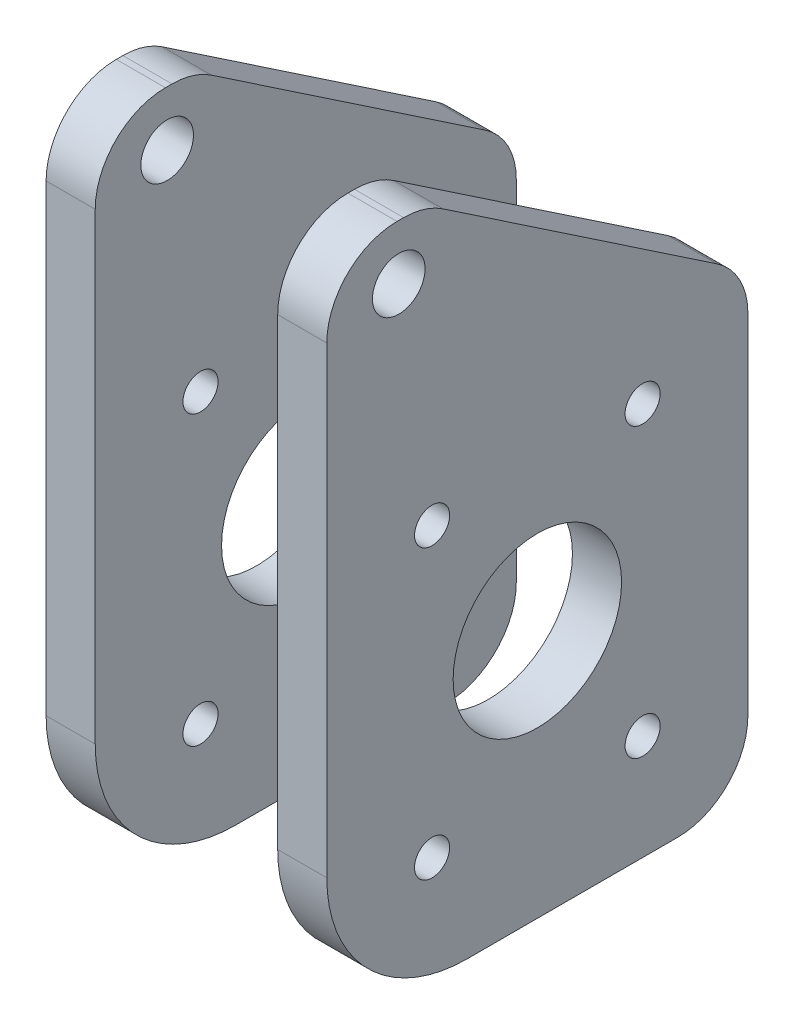
SolidWorks part; units mm, degrees
material "7075-T6, Plate (SS)"
ref_plane "Ground Plane" through (0, 0, 0) normal (0, 0, 1) x (1, 0, 0)
ref_plane "Side Plane" through (0, 0, 0) normal (0, 1, 0) x (1, 0, 0)
ref_plane "Rear Axle Centerline" through (0, 0, 0) normal (1, 0, 0) x (0, 0, -1)
sketch "Chassis Side View" plane through (0, 0, 0) normal (0, 1, 0) x (1, 0, 0)
  line L0 (0, -381) -> (2300, -381) construction
  line L1 (1150, -381) -> (1150, -856.742)
  line L2 (2150, -381) -> (2150, -1062.9307) construction
  line L3 (-753.0356, 0) -> (753.0356, 0) construction
  line L4 (2450, -381) -> (2450, -1062.9307) construction
  dimension "D1" = 2300
  dimension "D2" = 475.742
  dimension "D3" = 1150
  dimension "D4" = 381
  dimension "D5" = 150
  dimension "D6" = 150
ref_plane "Front Axle Centerline" through (2300, 0, 0) normal (1, 0, 0) x (0, 0, -1)
sketch "Front Wheel Assy Constraints" plane through (2300, 0, 0) normal (1, 0, 0) x (0, 0, -1)
  line L0 (0, 727.5) -> (0, 822.5)
  line L1 (0, 822.5) -> (-271.78, 822.5)
  line L2 (-271.78, 822.5) -> (-551.18, 822.5)
  line L3 (-551.18, 822.5) -> (-551.18, 727.5)
  line L4 (-551.18, 775) -> (0, 775) construction
  line L5 (-271.78, 822.5) -> (-271.78, 775) construction
  line L6 (-551.18, 727.5) -> (-445.4516, 727.5)
  line L7 (-445.4516, 727.5) -> (-445.4516, 798.5)
  line L8 (-445.4516, 798.5) -> (-105.7284, 798.5)
  line L9 (-105.7284, 798.5) -> (-105.7284, 727.5)
  line L10 (-105.7284, 727.5) -> (0, 727.5)
  line L11 (0, 0) -> (-673.9047, 0) construction
  line L13 (0, 753.0356) -> (0, -753.0356) construction
  dimension "D1" = 95
  dimension "D2" = 279.4
  dimension "D3" = 271.78
  dimension "D4" = 23.5
  dimension "D5" = 1550
sketch "Front Sus Front View" plane through (2300, 0, 0) normal (1, 0, 0) x (0, 0, -1)
  line L0 (0, 775) -> (0, 768.65) construction
  line L1 (0, 753.0356) -> (0, -753.0356) construction
  line L2 (0, 768.65) -> (-762, 634.2888) construction
  line L3 (0, 768.65) -> (-745.3671, 768.65) construction
  line L4 (-366.7919, -1090.2477) -> (-525.9451, 520.8571) construction
  line L5 (-366.7919, -1090.2477) -> (-379.5678, 520.8571) construction
  line L6 (-366.7919, -1090.2477) -> (0, 775) construction
  line L7 (-525.9451, 520.8571) -> (-541, 673.2571)
  line L8 (-379.5678, 520.8571) -> (-381, 701.4694)
  line L9 (0, 0) -> (-152.4, 0) construction
  line L13 (-525.9451, 520.8571) -> (-379.5678, 520.8571) construction
  dimension "D1" = 6.35
  dimension "D2" = 10
  dimension "D3" = 152.4
  dimension "D4" = 1865.2477
  dimension "D7" = 541
  dimension "D8" = 153.1418
  dimension "D5" = 152.4
ref_plane "Fron Wheel Side View Plane" through (0, 775, 0) normal (0, 1, 0) x (1, 0, 0)
sketch "Front SVSA" plane through (0, 775, 0) normal (0, 1, 0) x (1, 0, 0)
  line L0 (2271.684, -676.7175) -> (2328.316, 133.1575)
  line L1 (2300, 0) -> (2300, -771.0839) construction
  line L2 (2300, 0) -> (-2450.054, -116.0888) construction
  line L3 (-2450.054, -116.0888) -> (2298.2335, -297.0415) construction
  line L4 (-753.0356, 0) -> (753.0356, 0) construction
  point P5 (2300, -271.78)
  dimension "D1" = 4
  dimension "D2" = 1.4
  dimension "D3" = 4750.054
sketch3d "Front Chassis Side Axes"
  line L0 (2300, 520.8571, 379.5678) -> (2300, 701.4694, 381) construction
  line L1 (2300, 520.8571, 525.9451) -> (2300, 673.2571, 541) construction
  line L2 (2300, 520.8571, 379.5678) -> (2300, 701.4694, 381) construction
  line L3 (2300, 520.8571, 525.9451) -> (2300, 673.2571, 541) construction
  line L4 (2300, 673.2571, 541) -> (2300, 775, 551.0507) construction
  line L5 (2300, 701.4694, 381) -> (2300, 775, 381.5831) construction
  line L6 (2300, 775, 0) -> (2300, 775, 771.0839) construction
  line L7 (-2450.054, 775, 116.0888) -> (2349.7917, 775, 555.6101) construction
  line L8 (-2450.054, 775, 116.0888) -> (2349.9221, 775, 384.3734) construction
  line L9 (2349.9221, 775, 384.3734) -> (2177.377, 520.8571, 372.714) construction
  line L10 (2349.7917, 775, 555.6101) -> (2225.4174, 520.8571, 519.1156) construction
  line L11 (2300, 520.8571, 525.9451) -> (2300, 520.8571, 519.1156) construction
  line L12 (2300, 520.8571, 519.1156) -> (2225.4174, 520.8571, 519.1156) construction
  line L13 (2598.7501, 520.8571, 553.3017) -> (1702.4998, 520.8571, 471.2321)
  line L14 (2300, 520.8571, 379.5678) -> (2300, 520.8571, 372.714) construction
  line L15 (2300, 520.8571, 372.714) -> (2177.377, 520.8571, 372.714) construction
  line L16 (2599.5325, 520.8571, 396.3095) -> (1700.935, 520.8571, 346.0843)
  dimension "D1" = 50
  dimension "D2" = 50
  dimension "D3" = 600
  dimension "D4" = 300
  dimension "D5" = 600
  dimension "D6" = 300
sketch3d "Front Left Control Arm"
  line L0 (2300, 520.8571, 379.5678) -> (2300, 701.4694, 381) construction
  line L2 (2300, 520.8571, 379.5678) -> (2300, 701.4694, 381) construction
  line L3 (2300, 520.8571, 525.9451) -> (2300, 673.2571, 541) construction
  line L4 (2598.7501, 520.8571, 553.3017) -> (1702.4998, 520.8571, 471.2321) construction
  line L5 (2599.5325, 520.8571, 396.3095) -> (1700.935, 520.8571, 346.0843) construction
  line L6 (2598.7501, 520.8571, 553.3017) -> (1702.4998, 520.8571, 471.2321) construction
  line L7 (2599.5325, 520.8571, 396.3095) -> (1700.935, 520.8571, 346.0843) construction
  line L8 (2450, 520.8571, 539.6806) -> (2280.5957, 673.2571, 539.2232)
  line L9 (2280.5957, 673.2571, 539.2232) -> (2150, 520.8571, 512.2097)
  line L10 (2300, 520.8571, 525.9451) -> (2300, 673.2571, 541) construction
  line L11 (2300, 673.2571, 541) -> (2280.5957, 673.2571, 539.2232) construction
  line L12 (2271.684, 775, 676.7175) -> (2328.316, 775, -133.1575) construction
  line L13 (2150, 0, 512.2097) -> (2150, 520.8571, 512.2097) construction
  line L14 (2292.3517, 701.4694, 380.5725) -> (2292.3517, 775, 381.1556) construction
  line L15 (2150, 0, 381) -> (2150, 0, 1062.9307) construction
  line L16 (2450, 0, 539.6806) -> (2450, 520.8571, 539.6806) construction
  line L17 (2450, 0, 381) -> (2450, 0, 1062.9307) construction
  line L18 (2450, 520.8571, 387.9517) -> (2292.3517, 701.4694, 380.5725)
  line L19 (2292.3517, 701.4694, 380.5725) -> (2150, 520.8571, 371.1838)
  line L20 (2300, 701.4694, 381) -> (2292.3517, 701.4694, 380.5725) construction
  line L21 (2450, 0, 387.9517) -> (2450, 520.8571, 387.9517) construction
  line L22 (2150, 0, 371.1838) -> (2150, 520.8571, 371.1838) construction
  line L23 (2280.5957, 673.2571, 539.2232) -> (2280.5957, 775, 549.2738) construction
sketch3d "Front Control Arm"
  line L0 (2450, 520.8571, 387.9517) -> (2292.3517, 701.4694, 380.5725) construction
  line L1 (2292.3517, 701.4694, 380.5725) -> (2150, 520.8571, 371.1838) construction
  line L2 (2280.5957, 673.2571, 539.2232) -> (2150, 520.8571, 512.2097) construction
  line L3 (2450, 520.8571, 539.6806) -> (2280.5957, 673.2571, 539.2232) construction
  line L4 (2450, 520.8571, 387.9517) -> (2292.3517, 701.4694, 380.5725)
  line L5 (2292.3517, 701.4694, 380.5725) -> (2150, 520.8571, 371.1838)
  line L6 (2280.5957, 673.2571, 539.2232) -> (2150, 520.8571, 512.2097)
  line L7 (2450, 520.8571, 539.6806) -> (2280.5957, 673.2571, 539.2232)
  line L8 (2450, -520.8571, 539.6806) -> (2280.5957, -673.2571, 539.2232)
  line L9 (2280.5957, -673.2571, 539.2232) -> (2150, -520.8571, 512.2097)
  line L10 (2292.3517, -701.4694, 380.5725) -> (2150, -520.8571, 371.1838)
  line L11 (2450, -520.8571, 387.9517) -> (2292.3517, -701.4694, 380.5725)
ref_plane "Max Droop Plane" through (0, 0, -25.4) normal (0, 0, 1) x (1, 0, 0)
ref_plane "Plane3" through (2292.3517, 0, 0) normal (1, 0, 0) x (0, 0, -1)
sketch "Shock" plane through (2292.3517, 0, 0) normal (1, 0, 0) x (0, 0, -1)
  line L0 (-377.1418, 701.4343) -> (-411.0525, 664.6394) construction
  line L1 (-411.0525, 664.6394) -> (-543.5971, 520.822)
  line L3 (94.8273, 0) -> (-94.8273, 0) construction
  line L4 (-411.0525, -664.6394) -> (-543.5971, -520.822)
  dimension "D1" = 50.038
  dimension "D2" = 195.58
  dimension "D3" = 30.48
  dimension "D4" = 36.83
sketch3d "3DSketch1"
  line L0 (2292.3517, 701.4694, 380.5725) -> (2318.5484, 671.4568, 381.7987) construction
  line L1 (2450, 520.8571, 387.9517) -> (2292.3517, 701.4694, 380.5725) construction
  line L2 (2318.5484, 671.4568, 381.7987) -> (2292.3517, 664.6394, 411.0525) construction
  line L3 (2292.3517, 664.6394, 411.0525) -> (2267.7008, 670.193, 378.9467) construction
  line L4 (2292.3517, 701.4694, 380.5725) -> (2150, 520.8571, 371.1838) construction
  line L5 (2267.7008, 670.193, 378.9467) -> (2292.3517, 701.4694, 380.5725) construction
  line L6 (2318.5484, 671.4568, 381.7987) -> (2267.7008, 670.193, 378.9467) construction
  dimension "D1" = 40.857
  dimension "D2" = 39.8563
sketch3d "Parametric Analysis"
  line L2 (2300, 822.5, 0) -> (2300, 822.5, 271.78) construction
  line L3 (2300.4137, 822.5, 271.7939) -> (2300.4137, 822.5, -88.8537) construction
  line L4 (2450, 520.8571, 387.9517) -> (2292.3526, 701.4695, 380.5568)
  line L5 (2292.3526, 701.4695, 380.5568) -> (2150, 520.8571, 371.1838)
  line L6 (2450, 520.8571, 539.6806) -> (2280.5972, 673.2586, 539.2077)
  line L7 (2280.5972, 673.2586, 539.2077) -> (2150, 520.8571, 512.2097)
  line L8 (2292.3517, 701.4694, 380.5725) -> (2300, 822.5, 271.78) construction
  line L9 (2450, 520.8571, 387.9517) -> (2292.3517, 701.4694, 380.5725) construction
  line L10 (2292.3517, 701.4694, 380.5725) -> (2150, 520.8571, 371.1838) construction
  line L11 (2450, 520.8571, 539.6806) -> (2280.5957, 673.2571, 539.2232) construction
  line L12 (2280.5957, 673.2571, 539.2232) -> (2150, 520.8571, 512.2097) construction
  line L13 (2280.5957, 673.2571, 539.2232) -> (2292.3517, 701.4694, 380.5725) construction
  line L14 (2300, 822.5, 271.78) -> (2280.5957, 673.2571, 539.2232) construction
  line L15 (2300, 822.5, 271.78) -> (2300.4132, 720.8156, 271.78) construction
  line L16 (2280.5972, 673.2586, 539.2077) -> (2300.4137, 822.5, 271.7939) construction
  line L17 (2300.4137, 822.5, 271.7939) -> (2292.3526, 701.4695, 380.5568) construction
  line L18 (2280.5972, 673.2586, 539.2077) -> (2292.3526, 701.4695, 380.5568) construction
  line L19 (2300.4137, 822.5, 271.7939) -> (2300.4137, 720.8148, 271.7641) construction
  line L22 (2292.3517, 520.822, 543.5971) -> (2292.3524, 670.3521, 408.6413)
  line L23 (2292.3524, 670.3521, 408.6413) -> (2292.3526, 701.4695, 380.5568) construction
  line L29 (2292.3524, 670.3521, 408.6413) -> (2321.8231, 667.7059, 381.9392) construction
  line L30 (2321.8231, 667.7059, 381.9392) -> (2292.3526, 701.4695, 380.5568) construction
  line L31 (2271.4781, 674.9846, 379.1823) -> (2292.3526, 701.4695, 380.5568) construction
  line L32 (2271.4781, 674.9846, 379.1823) -> (2321.8231, 667.7059, 381.9392) construction
  line L33 (2292.3524, 670.3521, 408.6413) -> (2271.4781, 674.9846, 379.1823) construction
  line L37 (2318.5484, 671.4568, 381.7987) -> (2267.7008, 670.193, 378.9467) construction
  line L39 (2300.4137, 822.5, 271.7939) -> (2300.4137, 822.5798, 0.014)
  line L40 (2300.4137, 822.5798, 0.014) -> (2300.4137, 727.5798, -0.014)
  line L41 (2300, 727.5, 0) -> (2300, 822.5, 0) construction
  line L46 (2318.5484, 671.4568, 381.7987) -> (2292.3517, 664.6394, 411.0525) construction
  point P5 (2300.4137, 775.0798, 0)
  dimension "D1" = 25.4
  dimension "D3" = 201.4258
  dimension "D4" = 0.017
ref_plane "Plane1" through (0, 724.454, 0) normal (0, 1, 0) x (1, 0, 0)
sketch "Sketch1" plane through (0, 724.454, 0) normal (0, 1, 0) x (1, 0, 0)
  line L0 (2300, 0) -> (2300, -551.18) construction
  line L1 (2300, 0) -> (2300, -673.9047) construction
  line L2 (-753.0356, 0) -> (753.0356, 0) construction
  line L3 (2300, -275.59) -> (2280.5957, -539.2232) construction
  line L4 (2295.0737, -527.2852) -> (2266.1177, -527.2852)
  line L5 (2295.0737, -527.2852) -> (2319.6398, -484.4331)
  line L6 (2319.6398, -484.4331) -> (2343.1517, -404.3723)
  line L7 (2343.1517, -404.3723) -> (2343.1517, -356.7727)
  line L8 (2343.1517, -356.7727) -> (2320.6639, -270.2211)
  line L9 (2266.1177, -527.2852) -> (2241.5517, -484.4331)
  line L10 (2241.5517, -484.4331) -> (2241.5517, -356.7727)
  line L11 (2280.4102, -267.1009) -> (2241.5517, -356.7727)
  line L12 (2332.9917, -380.5725) -> (2251.7117, -380.5725) construction
  line L13 (2343.1517, -356.7727) -> (2241.5517, -356.7727) construction
  line L14 (2332.9917, -365.6119) -> (2251.7117, -365.6119)
  line L15 (2332.9917, -365.6119) -> (2332.9917, -395.5331)
  line L16 (2332.9917, -395.5331) -> (2251.7117, -395.5331)
  line L17 (2251.7117, -365.6119) -> (2251.7117, -395.5331)
  line L18 (2332.9917, -365.6119) -> (2251.7117, -395.5331) construction
  line L19 (2332.9917, -395.5331) -> (2251.7117, -365.6119) construction
  line L20 (2343.1517, -404.3723) -> (2241.5517, -404.3723) construction
  line L21 (2319.6398, -484.4331) -> (2241.5517, -484.4331) construction
  line L22 (2280.5957, -539.2232) -> (2280.5957, -527.2852) construction
  circle A0 centre (2300, -275.59) radius 15
  arc A1 (2320.6639, -270.2211) -> (2280.4102, -267.1009) centre (2300, -275.59) ccw
  arc A2 (2280.4102, -267.1009) -> (2320.6639, -270.2211) centre (2300, -275.59) ccw construction
  point P21 (2292.3517, -380.5725)
  point P30 (2292.3517, -380.5725)
  dimension "D1" = 30
  dimension "D2" = 42.7
  dimension "D3" = 81.28
  dimension "D4" = 29.9212
  dimension "D5" = 10.16
  dimension "D6" = 10.16
  dimension "D7" = 8.8392
  dimension "D8" = 8.8392
  dimension "D9" = 11.938
  dimension "D10" = 28.956
  dimension "D11" = 88.9
ref_plane "Plane4" through (2292.3517, 0, 0) normal (-1, 0, 0) x (0, 0, 1)
sketch "Sketch3" plane through (2292.3517, 0, 0) normal (-1, 0, 0) x (0, 0, 1)
  line L0 (556.6129, 408.838) -> (556.6129, 530.758)
  line L3 (480.4129, 491.388) -> (480.4129, 408.838)
  line L4 (480.4129, 408.838) -> (556.6129, 408.838)
  line L6 (537.5629, 479.958) -> (499.4629, 479.958) construction
  line L13 (556.6129, 530.758) -> (538.8329, 530.758)
  line L14 (538.8329, 530.758) -> (480.4129, 491.388)
  line L16 (537.5629, 479.958) -> (499.4629, 427.888) construction
  line L17 (499.4629, 479.958) -> (537.5629, 427.888) construction
  circle A0 centre (543.5971, 520.822) radius 4.7625
  circle A1 centre (537.5629, 479.958) radius 3.175
  circle A2 centre (537.5629, 427.888) radius 3.175
  circle A3 centre (499.4629, 427.888) radius 3.175
  circle A4 centre (499.4629, 479.958) radius 3.175
  circle A12 centre (518.5129, 453.923) radius 15.24
  point P28 (75.0078, 775.7838)
  dimension "D5" = 9.525
  dimension "D6" = 6.35
  dimension "D7" = 6.35
  dimension "D8" = 6.35
  dimension "D9" = 6.35
  dimension "D18" = 30.48
  dimension "D2" = 82.55
  dimension "D3" = 76.2
  dimension "D4" = 121.92
  dimension "D10" = 17.78
  dimension "D11" = 50.8
  dimension "D12" = 19.05
  dimension "D13" = 19.05
  dimension "D14" = 19.05
  dimension "D15" = 19.05
  dimension "D16" = 19.05
  dimension "D17" = 19.05
extrude "Boss-Extrude1" add sketch "Sketch3" along normal mid plane 50.8
fillet "Fillet1" radius 12.7 4 edges at (2292.3517, 408.838, 480.4129) (2292.3517, 491.388, 480.4129) (2292.3517, 530.758, 538.8329) (2292.3517, 530.758, 556.6129)
fillet "Fillet2" radius 25.4 1 edges at (2292.3517, 408.838, 556.6129)
sketch "Sketch4" plane through (0, 408.838, 0) normal (0, -1, 0) x (1, 0, 0)
  line L0 (2308.8617, 478.8299) -> (2308.8617, 576.5141)
  line L1 (2308.8617, 576.5141) -> (2275.8417, 576.5141)
  line L2 (2275.8417, 576.5141) -> (2275.8417, 478.8299)
  line L3 (2275.8417, 478.8299) -> (2308.8617, 478.8299)
  line L4 (2266.9517, 493.1129) -> (2266.9517, 531.2129) construction
  line L5 (2317.7517, 493.1129) -> (2317.7517, 531.2129) construction
  dimension "D1" = 8.89
  dimension "D2" = 8.89
extrude "Cut-Extrude1" cut sketch "Sketch4" against normal through all
equation "\"wheelbase\"= 2.3m"
equation "\"track_front_outer\"= 1.55m"
equation "\"cg_h\"= 18.73in"
equation "\"cg_b\"= \"wheelbase\" / 2"
equation "\"chassis_ride_height\"= 15in"
equation "\"hub_offset\"= 23.5mm"
equation "\"tire_radius\"= 11in"
equation "\"tire_radius_loaded\"= 10.7in"
equation "\"tire_width\"= 95mm"
equation "\"static_camber\"= 0deg"
equation "\"caster_static\"= 4deg"
equation "\"control_arm_ratio\"= 0.95"
equation "\"roll_center_height\"= 6in"
equation "\"scrub_radius\"= 0.25in"
equation "\"camber_change_rate\"= 0.5deg'per inch of travel"
equation "\"fvsa_length\"= atn ( 1 / \"camber_change_rate\" )"
equation "\"svsa_length\"= 2.5 * \"wheelbase\""
equation "\"svsa_height\"= 1"
equation "\"anti_squat_rear\"= 0.15"
equation "\"front_brakes\"= .75"
equation "\"anti_dive_front\"= 0.1"
equation "\"D1@Chassis Side View\" = \"wheelbase\""
equation "\"D2@Chassis Side View\" = \"cg_h\""
equation "\"D3@Chassis Side View\" = \"cg_b\""
equation "\"D4@Chassis Side View\" = \"chassis_ride_height\""
equation "\"D1@Front Axle Centerline\"=\"wheelbase\""
equation "\"D1@Front Wheel Assy Constraints\" = \"tire_width\""
equation "\"D2@Front Wheel Assy Constraints\" = \"tire_radius\""
equation "\"D3@Front Wheel Assy Constraints\" = \"tire_radius_loaded\""
equation "\"D4@Front Wheel Assy Constraints\" = \"hub_offset\""
equation "\"D1@Front Sus Front View\" = \"scrub_radius\""
equation "\"static_kingpin\"= 10deg"
equation "\"D2@Front Sus Front View\" = \"static_kingpin\""
equation "\"D3@Front Sus Front View\" = \"roll_center_height\""
equation "\"D6@Front Sus Front View\" = \"chassis_ride_height\""
equation "\"D7@Front Sus Front View\"=\"chassis_ride_height\" + 160mm"
equation "\"D1@Front SVSA\" = \"caster_static\""
equation "\"D4@Front Sus Front View\"=\"fvsa_length\"+10"
equation "\"D5@Front Wheel Assy Constraints\"=\"track_front_outer\""
equation "\"phi_front\"= atn ( \"anti_dive_front\" / \"front_brakes\" * \"cg_h\" / \"wheelbase\" )"
equation "\"anti_lift_rear\"= 0.1"
equation "\"a\"= 0"
